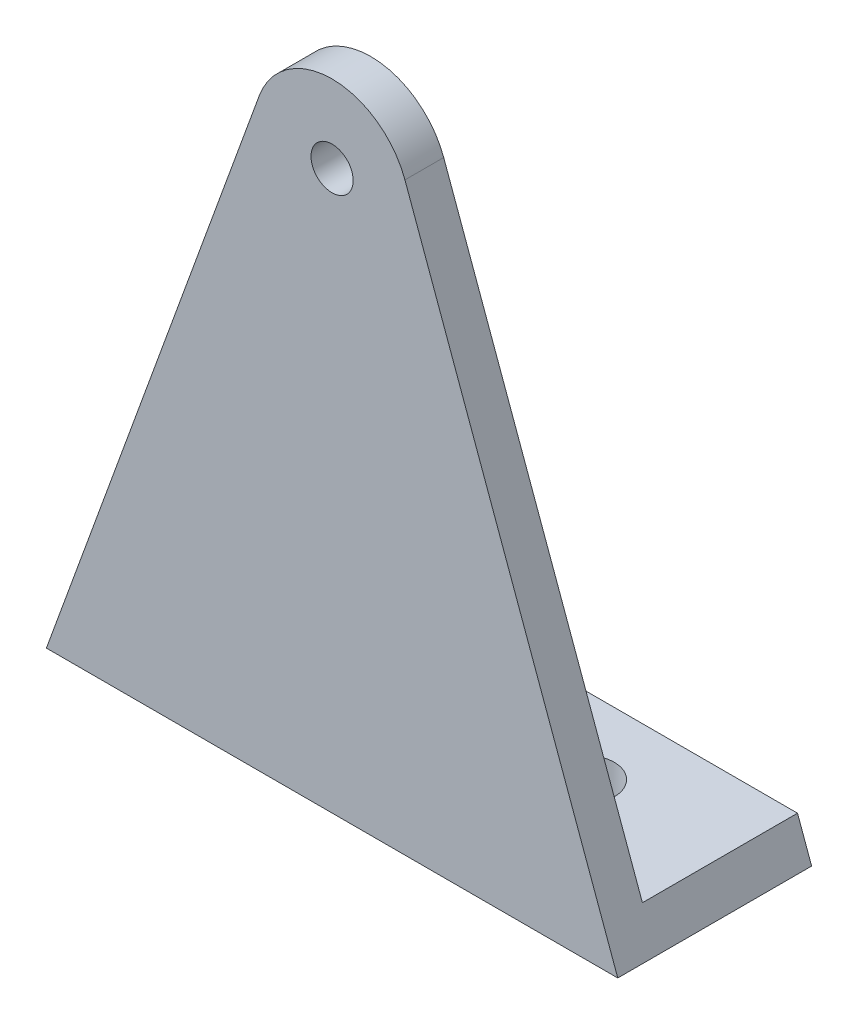
SolidWorks part; units mm, degrees
material "ABS"
ref_plane "Front Plane" through (0, 0, 0) normal (0, 0, 1) x (1, 0, 0)
ref_plane "Top Plane" through (0, 0, 0) normal (0, 1, 0) x (1, 0, 0)
ref_plane "Right Plane" through (0, 0, 0) normal (1, 0, 0) x (0, 0, -1)
sketch "Sketch1" plane through (0, 0, 0) normal (0, 0, 1) x (1, 0, 0)
  line L0 (-9.1496, 21.938) -> (-26.5808, -25.9538)
  line L1 (-26.5808, -25.9538) -> (20.2157, -25.9538)
  line L2 (20.2157, -25.9538) -> (2.7845, 21.938)
  arc A0 (2.7845, 21.938) -> (-9.1496, 21.938) centre (-3.1825, 19.7662) ccw
  point P7 (-3.1825, 19.7662)
  dimension "D3" = 6.35
  dimension "D1" = 70
  dimension "D2" = 70
  dimension "D4" = 45.72
extrude "Boss-Extrude1" add sketch "Sketch1" along normal blind 3.175
hole_wizard "Tap Drill for #8-32 Tap1" positions "3DSketch1" profile "Sketch2" hole size "#8-32" standard "ANSI Inch"
sketch3d "3DSketch1"
  line L0 (-3.1825, 19.7662, 3.175) -> (-3.1825, 19.7662, 0) construction
  point P0 (-3.1825, 19.7662, 0)
sketch "Sketch2" plane through (-3.1825, 19.7662, 0) normal (1, 0, 0) x (0, 1, 0)
  line L0 (0, 0) -> (0, 4.3398)
  line L1 (0, 4.3398) -> (1.7272, 3.302)
  line L2 (1.7272, 3.302) -> (1.7272, 0)
  line L5 (1.7272, 0) -> (0, 0)
  line L10 (0, 4.3398) -> (-1.7272, 3.302) construction
  line L11 (0, -6.35) -> (0, 107.95) construction
  dimension "Hole Dia." = 3.4544
  dimension "Hole Depth" = 3.302
  dimension "Drill Angle" = 118
sketch "Sketch3" plane through (0, 0, 0) normal (0, 0, -1) x (-1, 0, 0)
  line L0 (-19.0601, -22.7788) -> (-20.2157, -25.9538)
  line L1 (-20.2157, -25.9538) -> (-2.7845, 21.938) construction
  line L2 (-20.2157, -25.9538) -> (26.5808, -25.9538)
  line L3 (26.5808, -25.9538) -> (25.4252, -22.7788)
  line L4 (9.1496, 21.938) -> (26.5808, -25.9538) construction
  line L5 (25.4252, -22.7788) -> (-19.0601, -22.7788)
  line L6 (26.5808, -25.9538) -> (-20.2157, -25.9538) construction
  dimension "D1" = 3.175
extrude "Boss-Extrude2" add sketch "Sketch3" along normal blind 12.7
sketch "Sketch5" plane through (0, -22.7788, 0) normal (0, 1, 0) x (1, 0, 0)
  line L0 (-14.3039, 6.35) -> (-14.3039, 12.7) construction
  line L1 (-25.4252, 12.7) -> (19.0601, 12.7) construction
  line L2 (-14.3039, 6.35) -> (-25.4252, 6.35) construction
  line L3 (-25.4252, 12.7) -> (-25.4252, 0) construction
  line L4 (-14.3039, 6.35) -> (-3.1825, 6.35) construction
  line L5 (-3.1825, 6.35) -> (7.9388, 6.35) construction
  line L6 (7.9388, 6.35) -> (19.0601, 6.35) construction
  line L7 (19.0601, 12.7) -> (19.0601, 0) construction
  line L8 (-14.3039, 6.35) -> (-14.3039, 0) construction
  line L9 (-25.4252, 0) -> (19.0601, 0) construction
  point P0 (-14.3039, 6.35)
  point P1 (7.9388, 6.35)
hole_wizard "#8 Clearance Hole1" positions "3DSketch3" profile "Sketch7" hole size "#8" standard "ANSI Inch" end condition through all
sketch3d "3DSketch3"
  point P0 (-14.3039, -22.7788, -6.35)
  point P3 (7.9388, -22.7788, -6.35)
sketch "Sketch7" plane through (-14.3039, -22.7788, -6.35) normal (1, 0, 0) x (0, 0, 1)
  line L0 (0, 0) -> (0, 3.175)
  line L1 (0, 3.175) -> (2.4574, 3.175)
  line L2 (2.4574, 3.175) -> (2.4574, 0)
  line L5 (2.4574, 0) -> (0, 0)
  line L11 (0, -6.35) -> (0, 107.95) construction
  dimension "Thru Hole Dia." = 4.9149
  dimension "Thru Hole Depth" = 3.175
